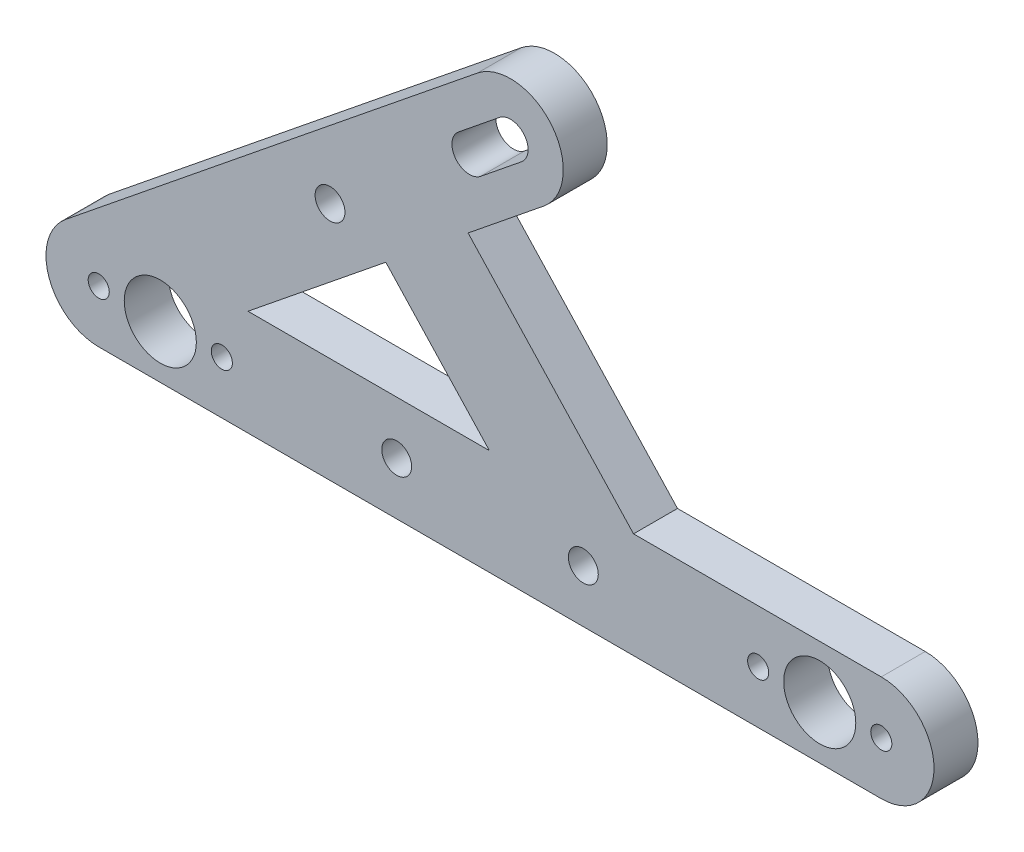
SolidWorks part; units mm, degrees
material "ABS PC"
ref_plane "Plan de face" through (0, 0, 0) normal (0, 0, 1) x (1, 0, 0)
ref_plane "Plan de dessus" through (0, 0, 0) normal (0, 1, 0) x (1, 0, 0)
ref_plane "Plan de droite" through (0, 0, 0) normal (1, 0, 0) x (0, 0, -1)
sketch "Esquisse1" plane through (0, 0, 0) normal (0, 0, 1) x (1, 0, 0)
  line L0 (-44.5, 0) -> (44.5, 0) construction
  line L1 (-27.526, 6) -> (-11.8498, 18.665)
  line L2 (-44.5, -6) -> (44.5, -6)
  line L3 (-44.5, 0) -> (2.3336, 37.8374) construction
  line L4 (2.3336, 37.8374) -> (-2.3336, 34.0668) construction
  line L5 (3.5905, 36.2817) -> (-1.0767, 32.511)
  line L6 (1.0767, 39.3931) -> (-3.5905, 35.6225)
  line L7 (-48.2706, 4.6671) -> (-1.4371, 42.5046)
  line L9 (-11.2683, 26.8483) -> (13.7115, 0) construction
  line L10 (-2.4927, 26.2247) -> (6.1042, 33.1703)
  line L11 (-11.8498, 18.665) -> (-0.0663, 6)
  line L12 (2.3336, 37.8374) -> (37.5, 0) construction
  line L13 (-2.4927, 26.2247) -> (16.3244, 6)
  line L14 (-27.526, 6) -> (-0.0663, 6)
  line L15 (16.3244, 6) -> (44.5, 6)
  arc A7 (-48.2706, 4.6671) -> (-44.5, -6) centre (-44.5, 0) ccw
  arc A8 (44.5, -6) -> (44.5, 6) centre (44.5, 0) ccw
  arc A9 (3.5905, 36.2817) -> (1.0767, 39.3931) centre (2.3336, 37.8374) ccw
  arc A10 (-3.5905, 35.6225) -> (-1.0767, 32.511) centre (-2.3336, 34.0668) ccw
  arc A11 (-48.2706, 4.6671) -> (-44.5, -6) centre (-44.5, 0) ccw
  arc A12 (6.1042, 33.1703) -> (-1.4371, 42.5046) centre (2.3336, 37.8374) ccw
  point P0 (0, 0)
  point P3 (0, 35.9521)
  point P9 (-37.5, 0)
  point P17 (0, 0)
  point P25 (0, 35.9521)
  point P31 (-21.0832, 18.9187)
  dimension "D4" = 82
  dimension "D5" = 44.5
  dimension "D6" = 38.935
  dimension "D8" = 12
  dimension "D10" = 7
  dimension "D11" = 12
  dimension "D14" = 6
  dimension "D18" = 6
  dimension "D15" = 6
  dimension "D2" = 51.95
  dimension "D7" = 94
  dimension "D9" = 12
  dimension "D13" = 12.665
  dimension "D16" = 4
  dimension "D17" = 6
  dimension "D19" = 57.2084
  dimension "D20" = 75
  dimension "D21" = 27.6247
extrude "Boss.-Extru.2" add sketch "Esquisse1" along normal blind 5 contours L10 A12 L7 A7 L2 A8 L15 L13 L14 L1 L11 A10 L6 A9 L5
hole_wizard "Dégagement M21" positions "Esquisse3" profile "Esquisse2" hole size "M2" standard "ISO"
sketch "Esquisse3" plane through (0, 0, 0) normal (0, 0, -1) x (-1, 0, 0)
  circle A0 centre (44.5, 0) radius 1.25 construction
  circle A1 centre (30.5, 0) radius 1.55 construction
  point P0 (44.5, 0)
  point P1 (30.5, 0)
sketch "Esquisse2" plane through (-44.5, 0, 0) normal (1, 0, 0) x (0, 1, 0)
  line L0 (0, 0) -> (0, 10.721)
  line L1 (0, 10.721) -> (1.2, 10)
  line L2 (1.2, 10) -> (1.2, 0)
  line L5 (1.2, 0) -> (0, 0)
  line L10 (0, 10.721) -> (-1.2, 10) construction
  line L11 (0, -6.35) -> (0, 107.95) construction
  dimension "Diamètre du perçage" = 2.4
  dimension "Profondeur du perçage" = 10
  dimension "Angle de pointe" = 118
hole_wizard "Dégagement M81" positions "Esquisse5" profile "Esquisse4" hole size "M8" standard "ISO"
sketch "Esquisse5" plane through (0, 0, 0) normal (0, 0, -1) x (-1, 0, 0)
  circle A0 centre (37.5, 0) radius 2.3 construction
  point P0 (37.5, 0)
sketch "Esquisse4" plane through (-37.5, 0, 0) normal (1, 0, 0) x (0, 1, 0)
  line L0 (0, 0) -> (0, 12.4635)
  line L1 (0, 12.4635) -> (4.1, 10)
  line L2 (4.1, 10) -> (4.1, 0)
  line L5 (4.1, 0) -> (0, 0)
  line L10 (0, 12.4635) -> (-4.1, 10) construction
  line L11 (0, -6.35) -> (0, 107.95) construction
  dimension "Diamètre du perçage" = 8.2
  dimension "Profondeur du perçage" = 10
  dimension "Angle de pointe" = 118
hole_wizard "Dégagement M22" positions "Esquisse9" profile "Esquisse8" hole size "M2" standard "ISO"
sketch "Esquisse9" plane through (0, 0, 0) normal (0, 0, -1) x (-1, 0, 0)
  circle A0 centre (-30.5, 0) radius 1.55 construction
  circle A1 centre (-44.5, 0) radius 1.55 construction
  point P0 (-44.5, 0)
  point P1 (-30.5, 0)
sketch "Esquisse8" plane through (44.5, 0, 0) normal (1, 0, 0) x (0, 1, 0)
  line L0 (0, 0) -> (0, 10.721)
  line L1 (0, 10.721) -> (1.2, 10)
  line L2 (1.2, 10) -> (1.2, 0)
  line L5 (1.2, 0) -> (0, 0)
  line L10 (0, 10.721) -> (-1.2, 10) construction
  line L11 (0, -6.35) -> (0, 107.95) construction
  dimension "Diamètre du perçage" = 2.4
  dimension "Profondeur du perçage" = 10
  dimension "Angle de pointe" = 118
hole_wizard "Dégagement M82" positions "Esquisse11" profile "Esquisse10" hole size "M8" standard "ISO"
sketch "Esquisse11" plane through (0, 0, 5) normal (0, 0, 1) x (1, 0, 0)
  circle A0 centre (37.5, 0) radius 3.5 construction
  point P0 (37.5, 0)
sketch "Esquisse10" plane through (37.5, 0, 5) normal (1, 0, 0) x (0, -1, 0)
  line L0 (0, 0) -> (0, 12.4635)
  line L1 (0, 12.4635) -> (4.1, 10)
  line L2 (4.1, 10) -> (4.1, 0)
  line L5 (4.1, 0) -> (0, 0)
  line L10 (0, 12.4635) -> (-4.1, 10) construction
  line L11 (0, -6.35) -> (0, 107.95) construction
  dimension "Diamètre du perçage" = 8.2
  dimension "Profondeur du perçage" = 10
  dimension "Angle de pointe" = 118
hole_wizard "Dégagement M31" positions "Esquisse13" profile "Esquisse12" hole size "M3" standard "ISO"
sketch "Esquisse13" plane through (0, 0, 5) normal (0, 0, 1) x (1, 0, 0)
  circle A0 centre (-18.1923, 21.2543) radius 1.5 construction
  point P0 (-18.1923, 21.2543)
  point P1 (10.6132, 0)
  point P4 (-10.6132, 0)
sketch "Esquisse12" plane through (-18.1923, 21.2543, 5) normal (1, 0, 0) x (0, -1, 0)
  line L0 (0, 0) -> (0, 6.0215)
  line L1 (0, 6.0215) -> (1.7, 5)
  line L2 (1.7, 5) -> (1.7, 0)
  line L5 (1.7, 0) -> (0, 0)
  line L10 (0, 6.0215) -> (-1.7, 5) construction
  line L11 (0, -6.35) -> (0, 107.95) construction
  dimension "Diamètre du perçage" = 3.4
  dimension "Profondeur du perçage" = 5
  dimension "Angle de pointe" = 118
